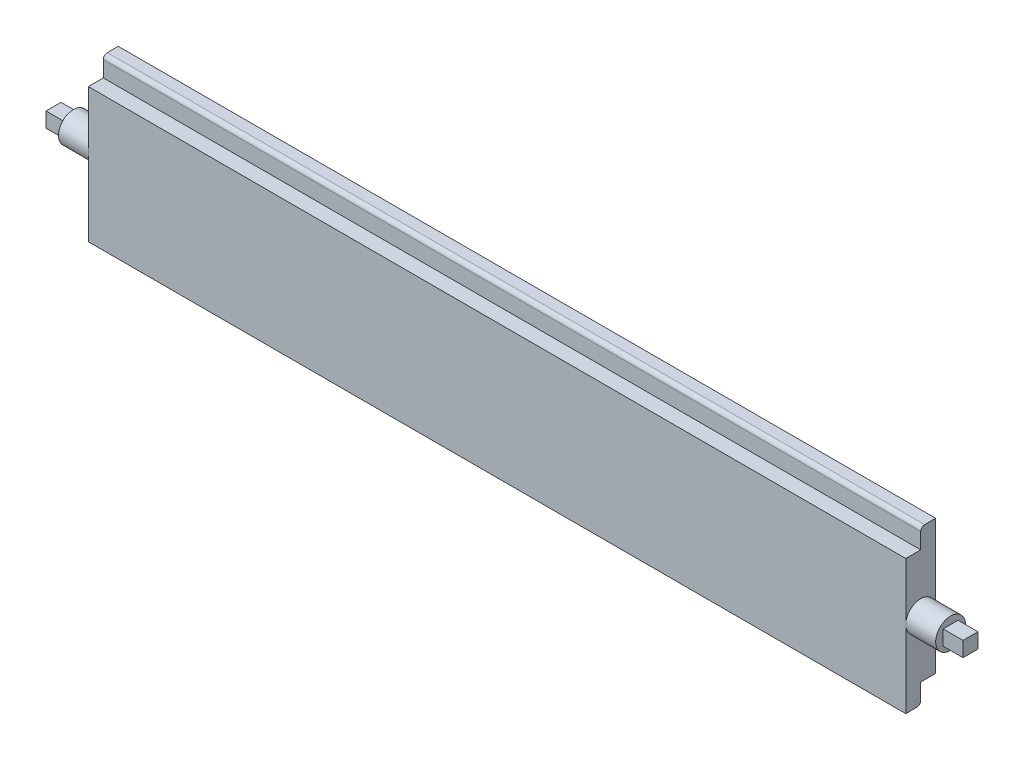
SolidWorks part; units mm, degrees
ref_plane "Front Plane" through (0, 0, 0) normal (0, 0, 1) x (1, 0, 0)
ref_plane "Top Plane" through (0, 0, 0) normal (0, 1, 0) x (1, 0, 0)
ref_plane "Right Plane" through (0, 0, 0) normal (1, 0, 0) x (0, 0, -1)
sketch "Sketch1" plane through (0, 0, 0) normal (0, 0, 1) x (1, 0, 0)
  line L1 (-130.302, -24.5999) -> (130.302, -24.5999)
  line L2 (-130.302, -24.5999) -> (-130.302, 24.5999)
  line L3 (-130.302, 24.5999) -> (130.302, 24.5999)
  line L4 (130.302, -24.5999) -> (130.302, 24.5999)
  line L5 (-130.302, -24.5999) -> (130.302, 24.5999) construction
  line L6 (-130.302, 24.5999) -> (130.302, -24.5999) construction
  point P0 (0, 0)
  dimension "D1" = 49.1998
  dimension "D2" = 260.604
extrude "Boss-Extrude1" add sketch "Sketch1" along normal mid plane 9.525
sketch "Sketch2" plane through (130.302, 0, 0) normal (1, 0, 0) x (0, 0, -1)
  line L0 (0, 50.8) -> (0, 23.0111) construction
  line L2 (-4.7625, 0) -> (8.5114, 0) construction
  circle A0 centre (0, 0) radius 4.7625
  dimension "D1" = 9.525
extrude "Boss-Extrude2" add sketch "Sketch2" along normal blind 9.525
sketch "Sketch3" plane through (139.827, 0, 0) normal (1, 0, 0) x (0, 0, -1)
  line L5 (-2.3876, -2.3876) -> (2.3876, -2.3876)
  line L6 (-2.3876, -2.3876) -> (-2.3876, 2.3876)
  line L7 (-2.3876, 2.3876) -> (2.3876, 2.3876)
  line L8 (2.3876, -2.3876) -> (2.3876, 2.3876)
  line L9 (-2.3876, -2.3876) -> (2.3876, 2.3876) construction
  line L10 (-2.3876, 2.3876) -> (2.3876, -2.3876) construction
  point P0 (0, 0)
  dimension "D1" = 4.7752
  dimension "D2" = 4.7752
extrude "Boss-Extrude3" add sketch "Sketch3" along normal blind 6.35
mirror "Mirror1" about plane through (0, 0, 0) normal (1, 0, 0) of "Boss-Extrude3", "Boss-Extrude2"
sketch "Sketch4" plane through (0, 0, 4.7625) normal (0, 0, 1) x (1, 0, 0)
  line L0 (130.302, 0) -> (130.302, 24.5999) construction
  line L1 (-130.302, 24.5999) -> (130.302, 24.5999)
  line L2 (-130.302, 24.5999) -> (-130.302, 18.2499)
  line L3 (-130.302, 18.2499) -> (130.302, 18.2499)
  line L4 (130.302, 24.5999) -> (130.302, 18.2499)
  dimension "D1" = 6.35
extrude "Cut-Extrude1" cut sketch "Sketch4" against normal blind 4.7625
sketch "Sketch5" plane through (0, 0, -4.7625) normal (0, 0, -1) x (-1, 0, 0)
  line L0 (130.302, 0) -> (130.302, -24.5999) construction
  line L1 (-130.302, -24.5999) -> (130.302, -24.5999)
  line L2 (-130.302, -24.5999) -> (-130.302, -18.2499)
  line L3 (-130.302, -18.2499) -> (130.302, -18.2499)
  line L4 (130.302, -24.5999) -> (130.302, -18.2499)
  dimension "D1" = 6.35
extrude "Cut-Extrude2" cut sketch "Sketch5" against normal blind 4.7625
fillet "Fillet1" radius 1.27 2 edges at (0, -24.5999, 0) (0, 24.5999, 0)
